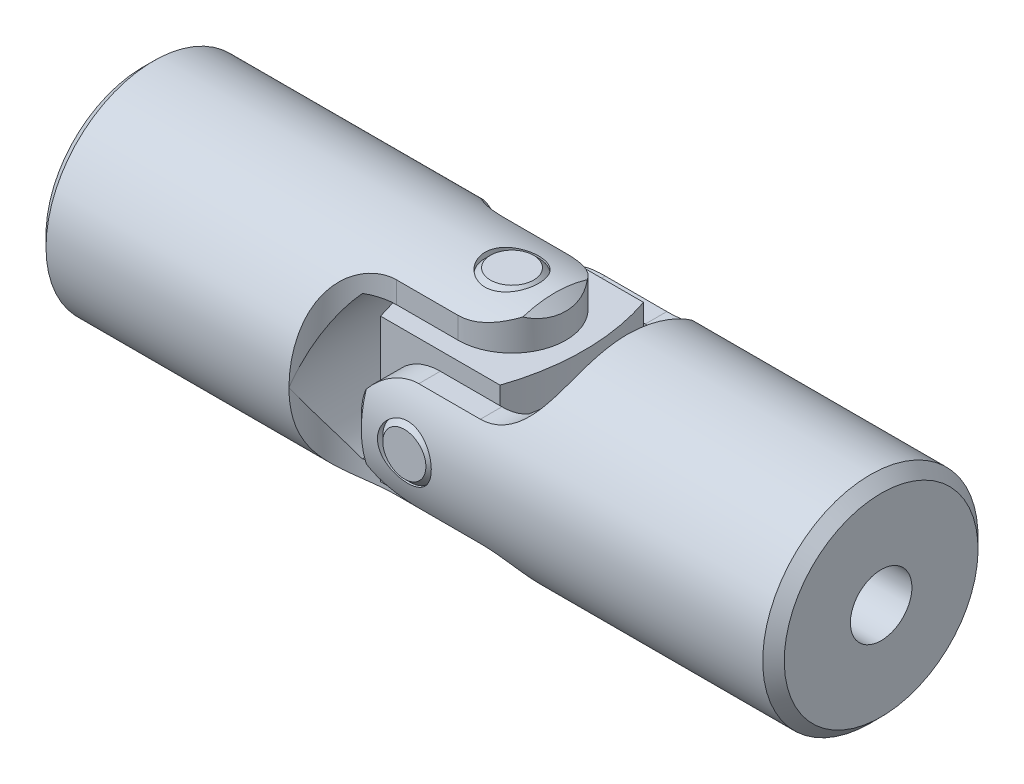
SolidWorks part; units mm, degrees
ref_plane "Front Plane" through (0, 0, 0) normal (0, 0, 1) x (1, 0, 0)
ref_plane "Top Plane" through (0, 0, 0) normal (0, 1, 0) x (1, 0, 0)
ref_plane "Right Plane" through (0, 0, 0) normal (1, 0, 0) x (0, 0, -1)
sketch "Sketch0" plane through (0, 0, 0) normal (0, 1, 0) x (1, 0, 0)
  line L0 (-38.1, 0) -> (38.1, 0) construction
  line L1 (-38.1, 11.1125) -> (-38.1, -11.1125) construction
  line L2 (-12.7, 3.175) -> (-12.7, -3.175) construction
  line L3 (-12.7, 3.175) -> (-9.525, 0) construction
  line L4 (-9.525, 0) -> (-12.7, -3.175) construction
  line L5 (-11.1125, 1.5875) -> (-11.1125, -1.5875) construction
  point P7 (-12.7, 0)
  point P8 (0, 0)
  point P12 (-11.1125, 0)
  dimension "D1" = 6.35
sketch "Sketch1" plane through (0, 0, 0) normal (0, 1, 0) x (1, 0, 0)
  line L0 (-38.1, 11.1125) -> (-11.9063, 11.1125)
  line L1 (5.5562, 11.1125) -> (5.5562, 0)
  line L2 (5.5562, 0) -> (-38.1, 0)
  line L3 (-38.1, 0) -> (-38.1, 11.1125)
  line L4 (-38.1, 11.1125) -> (-38.1, -11.1125) construction
  line L5 (-38.1, 0) -> (38.1, 0) construction
  line L6 (-11.9063, 11.1125) -> (5.5562, 11.1125)
  line L7 (-11.9063, 1.5875) -> (-11.9063, 11.1125) construction
  line L11 (0, 0) -> (11.1125, 0) construction
  line L12 (-11.1125, 1.5875) -> (-12.7, 1.5875) construction
  line L13 (-12.7, 3.175) -> (-12.7, -3.175) construction
  circle A0 centre (0, 0) radius 11.1125 construction
  dimension "D3" = 43.6562
revolve "Revolve1" add sketch "Sketch1" angle 360 about L0
chamfer "Chamfer1" distance 1.1112 angle 45 2 edges at (-38.1, 0, 11.1125) (5.5562, 0, 11.1125)
sketch "Sketch2" plane through (0, 0, 0) normal (0, 1, 0) x (1, 0, 0)
  line L0 (-36.9887, 11.1125) -> (-11.9126, 11.1125) construction
  line L1 (-11.9063, 11.1125) -> (5.5562, 11.1125) construction
  line L2 (4.445, 11.1125) -> (-36.9887, 11.1125) construction
  line L4 (-38.1, 0) -> (5.5562, 0) construction
  line L5 (-11.9126, 11.1125) -> (11.1125, 11.1125)
  line L6 (11.1125, 11.1125) -> (11.1125, -11.1125)
  line L7 (11.1125, -11.1125) -> (-11.9126, -11.1125)
  line L8 (0, 5.5562) -> (0, 0) construction
  line L9 (0, 5.5562) -> (-6.3564, 5.5562)
  line L10 (-11.9126, 11.1125) -> (-11.9126, -11.1125) construction
  line L11 (0, -5.5562) -> (-6.3564, -5.5562)
  arc A0 (-11.9126, 11.1125) -> (-6.3564, 5.5562) centre (-6.3564, 11.1125) ccw
  arc A1 (0, -5.5562) -> (0, 5.5562) centre (0, 0) ccw
  arc A2 (-6.3564, -5.5562) -> (-11.9126, -11.1125) centre (-6.3564, -11.1125) ccw
  dimension "D1" = 11.1125
  dimension "D" = 26.1874
extrude "Extrude1" cut sketch "Sketch2" against normal through all and the other way through all
sketch "Sketch3" plane through (0, 0, 0) normal (0, 0, 1) x (1, 0, 0)
  line L0 (-9.1345, 7.4009) -> (-11.9126, 4.6228) construction
  line L1 (-9.1345, 7.4009) -> (11.1125, 7.4009)
  line L2 (-11.9126, 4.6228) -> (-11.9126, -4.6228) construction
  line L3 (-9.1345, -7.4009) -> (11.1125, -7.4009)
  line L4 (11.1125, 7.4009) -> (11.1125, -7.4009)
  line L5 (-11.9126, -4.6228) -> (-9.1345, -7.4009) construction
  line L6 (-11.9126, 0) -> (-6.3564, 0) construction
  line L7 (-6.3564, -9.6237) -> (-6.3564, 9.6237) construction
  line L8 (11.1125, 0) -> (-11.9126, 0) construction
  line L9 (-9.1345, 0) -> (-9.1345, 7.4009) construction
  arc A0 (-9.1345, 7.4009) -> (-9.1345, -7.4009) centre (-0.6655, 0) ccw
  dimension "D1" = 14.8018
extrude "Extrude3" cut sketch "Sketch3" against normal through all and the other way through all
sketch "Sketch4" plane through (-38.1, 0, 0) normal (-1, 0, 0) x (0, 0, 1)
  circle A0 centre (0, 0) radius 3.175
  circle A1 centre (0, 0) radius 6.35 construction
  dimension "Max Bore Dia" = 12.7
extrude "Extrude4" cut sketch "Sketch4" against normal blind 6.35
sketch "Sketch5" plane through (-31.75, 0, 0) normal (-1, 0, 0) x (0, 0, 1)
  circle A0 centre (0, 0) radius 3.175 construction
  circle A1 centre (0, 0) radius 3.175
extrude "Extrude5" cut sketch "Sketch5" against normal through all draft 45
sketch "Sketch6" plane through (0, 0, 0) normal (0, 1, 0) x (1, 0, 0)
  line L0 (-38.1, 0) -> (38.1, 0) construction
  line L1 (5.5562, 0) -> (2.7781, 0) construction
  line L2 (2.7781, 0) -> (0, 0) construction
  circle A0 centre (0, 0) radius 2.7781
  arc A1 (0, -5.5562) -> (0, 5.5562) centre (0, 0) ccw construction
  dimension "D1" = 5.5562
extrude "Extrude6" cut sketch "Sketch6" against normal through all and the other way through all
mirror "Mirror1" about plane through (0, 0, 0) normal (1, 0, 0) of bodies 109 122
move or copy body "Body-Move/Copy1" bodies to move or copy 110 copy no rotation origin (0, 0, 0) rotation axis (1, 0, 0) rotation angle 90
sketch "Sketch18" plane through (0, 0, 0) normal (0, 1, 0) x (1, 0, 0)
  line L8 (0, 0) -> (38.1, 0) construction
  line L10 (-12.7, 3.175) -> (-38.1, 3.175)
  line L12 (-12.7, 3.175) -> (-12.7, -3.175)
  line L13 (-12.7, -3.175) -> (-38.1, -3.175)
  line L14 (-38.1, 11.1125) -> (-38.1, -11.1125) construction
  line L15 (0, 0) -> (0, 21.9558) construction
  line L16 (12.7, -3.175) -> (38.1, -3.175)
  line L17 (12.7, 3.175) -> (12.7, -3.175)
  line L18 (12.7, 3.175) -> (38.1, 3.175)
sketch "Sketch10" plane through (0, 0, 0) normal (0, 0, 1) x (1, 0, 0)
  line L0 (-7.4009, 7.4009) -> (7.4009, -7.4009) construction
  line L1 (-7.4009, 7.4009) -> (7.4009, 7.4009)
  line L2 (-7.4009, 7.4009) -> (-7.4009, -7.4009)
  line L3 (-7.4009, -7.4009) -> (7.4009, -7.4009)
  line L4 (7.4009, 7.4009) -> (7.4009, -7.4009)
  line L5 (0, 7.4009) -> (5.5562, 7.4009) construction
extrude "Extrude10" add sketch "Sketch10" against normal up to surface and the other way up to surface separate body
sketch "Sketch20" plane through (0, 7.4009, 0) normal (0, 1, 0) x (1, 0, 0)
  line L4 (7.4009, 7.4009) -> (-7.4009, 7.4009) construction
  line L5 (7.4009, -7.4009) -> (-7.4009, -7.4009) construction
  line L6 (-7.4009, 7.4009) -> (-7.4009, -7.4009) construction
  line L7 (7.4009, 7.4009) -> (7.4009, -7.4009) construction
  line L8 (8.4169, -8.4169) -> (8.4169, 8.4169)
  line L9 (8.4169, 8.4169) -> (-8.4169, 8.4169)
  line L10 (-8.4169, 8.4169) -> (-8.4169, -8.4169)
  line L11 (-8.4169, -8.4169) -> (8.4169, -8.4169)
  line L12 (8.4169, -8.4169) -> (8.4169, 8.4169)
  line L13 (8.4169, 8.4169) -> (6.1674, 8.4169)
  line L14 (-8.4169, 8.4169) -> (-8.4169, -8.4169)
  line L15 (-8.4169, -8.4169) -> (-6.1674, -8.4169)
  line L16 (-6.1674, 7.4009) -> (-6.1674, 8.4169)
  line L17 (6.1674, 7.4009) -> (6.1674, 8.4169)
  line L18 (6.1674, -7.4009) -> (6.1674, -8.4169)
  line L19 (-6.1674, -7.4009) -> (-6.1674, -8.4169)
  line L20 (-6.1674, 8.4169) -> (-8.4169, 8.4169)
  line L21 (6.1674, -8.4169) -> (8.4169, -8.4169)
  line L22 (-38.1, 0) -> (5.5562, 0) construction
  line L23 (7.4009, 7.4009) -> (-7.4009, 7.4009) construction
  arc A0 (6.1674, 7.4009) -> (6.1674, -7.4009) centre (-15.4186, 0) cw
  arc A1 (-6.1674, 7.4009) -> (-6.1674, -7.4009) centre (15.4186, 0) ccw
  dimension "D2" = 14.8018
  dimension "D3" = 1.2335
extrude "Cut-Extrude2" cut sketch "Sketch20" against normal through all
sketch "Sketch13" plane through (0, 0, 0) normal (0, 1, 0) x (1, 0, 0)
  circle A0 centre (0, 0) radius 2.7781 construction
  circle A1 centre (0, 0) radius 2.7781
extrude "Extrude13" cut sketch "Sketch13" against normal through all and the other way through all
sketch "Sketch14" plane through (0, 0, 0) normal (0, 1, 0) x (1, 0, 0)
  circle A1 centre (0, 0) radius 2.7781
  circle A2 centre (0, 0) radius 2.7781
  dimension "D1" = 0
extrude "Extrude14" add sketch "Sketch14" along normal mid plane 22.225 separate body
sketch "Sketch15" plane through (0, 0, 0) normal (0, 0, 1) x (1, 0, 0)
  circle A0 centre (0, 0) radius 2.7781 construction
  circle A1 centre (0, 0) radius 2.7781
extrude "Extrude15" cut sketch "Sketch15" against normal through all and the other way through all
sketch "Sketch16" plane through (0, 0, 0) normal (0, 0, 1) x (1, 0, 0)
  circle A1 centre (0, 0) radius 2.7781
  circle A2 centre (0, 0) radius 2.7781
  dimension "D1" = 0
extrude "Extrude16" add sketch "Sketch16" along normal mid plane 22.225
chamfer "Chamfer3" distance 0.5556 angle 45 4 edges at (0, -11.1125, 2.7781) (0, 11.1125, 2.7781) (2.7781, 0, 11.1125) (2.7781, 0, -11.1125)
move or copy body "Body-Move/Copy2" [suppressed] bodies to move or copy 111 copy no rotation origin (0, 0, 0) rotation axis (0, 0, -1) rotation angle 35
equation "\"D2@Sketch3\" = \"D1@Sketch3\" / 4"
equation "\"D1@Extrude14\" = \"OD@Sketch0\""
equation "\"D1@Extrude16\" = \"D1@Extrude14\""
equation "\"D1@Sketch3\" = \"OD@Sketch0\"*.666"
equation "\"D1@Chamfer1\" = \"OD@Sketch0\"/20"
equation "\"D1@Chamfer3\" = \"D1@Chamfer1\"*.50"
equation "\"D3@Sketch20\" = \"D2@Sketch20\"/12"
